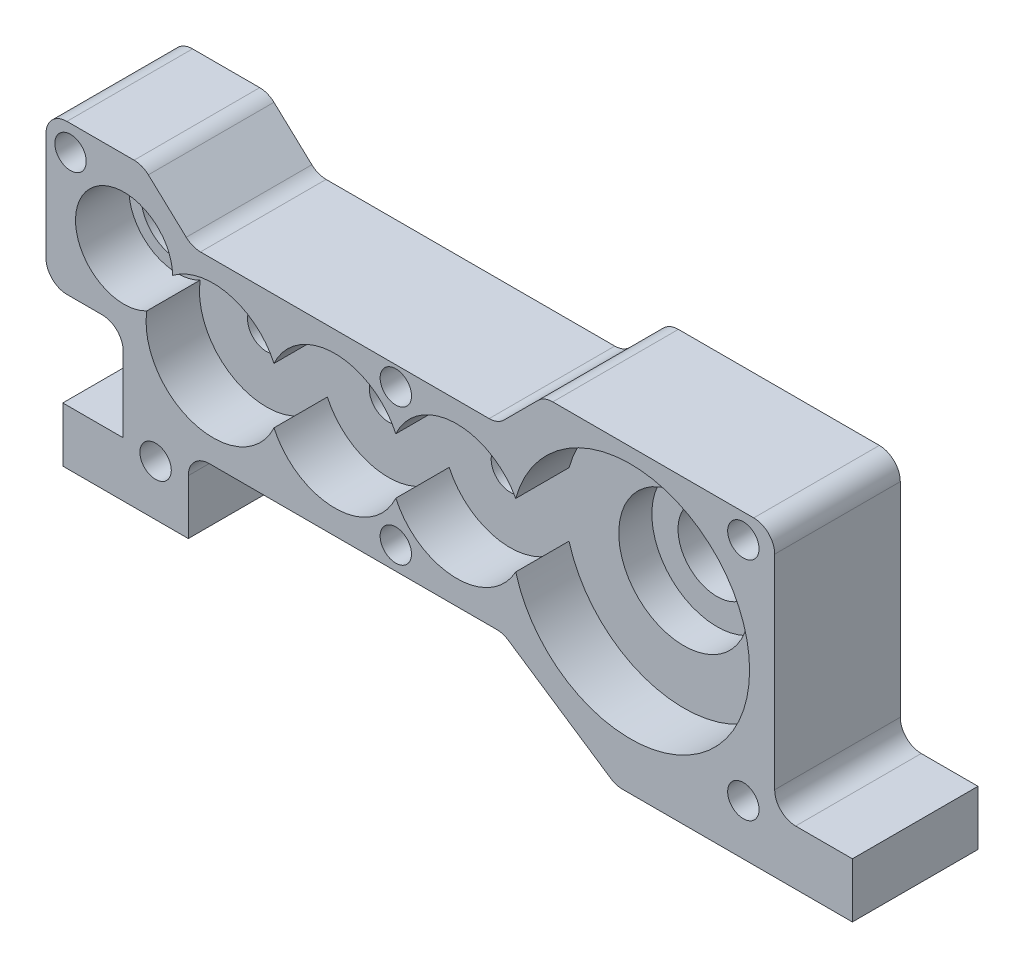
SolidWorks part; units mm, degrees
ref_plane "Front Plane" through (0, 0, 0) normal (0, 0, 1) x (1, 0, 0)
ref_plane "Top Plane" through (0, 0, 0) normal (0, 1, 0) x (1, 0, 0)
ref_plane "Right Plane" through (0, 0, 0) normal (1, 0, 0) x (0, 0, -1)
sketch "Sketch11" plane through (0, 0, 0) normal (0, 0, 1) x (1, 0, 0)
  arc A16 (19.459, 4.3148) -> (4.9137, 3.8376) centre (12.3051, 0.4566) ccw
  arc A17 (4.9137, 3.8376) -> (-9.8691, 3.8376) centre (-2.4777, 0.4566) ccw
  arc A18 (-9.8691, 3.8376) -> (-22.1638, 6.939) centre (-17.2605, 0.4566) ccw
  arc A19 (-22.1638, 6.939) -> (-25.3015, 1.6425) centre (-28.056, 6.8519) ccw
  arc A20 (-25.3015, 1.6425) -> (-9.8691, -2.9245) centre (-17.2605, 0.4566) ccw
  arc A21 (-9.8691, -2.9245) -> (4.9137, -2.9245) centre (-2.4777, 0.4566) ccw
  arc A22 (4.9137, -2.9245) -> (19.459, -3.4017) centre (12.3051, 0.4566) ccw
  arc A23 (19.459, -3.4017) -> (19.459, 4.3148) centre (33.3871, 0.4566) ccw
sketch "Sketch4" plane through (0, 0, 0) normal (0, 0, 1) x (1, 0, 0)
  line L0 (-34.99, 16.7149) -> (-26.8379, 16.7149)
  line L1 (-35.4928, -19.7615) -> (-20.2632, -19.7615)
  line L2 (22.1632, 15.9709) -> (18.0348, 11.8425)
  line L3 (-37.53, 14.1749) -> (-37.53, 1.0668)
  line L4 (50.8827, -10.5807) -> (50.8827, 14.1749)
  line L5 (60.3115, -19.7615) -> (60.3115, -13.1207)
  line L6 (60.3115, -13.1207) -> (53.4227, -13.1207)
  line L7 (-35.4928, -19.7615) -> (-35.4928, -13.1207)
  line L8 (-35.4928, -13.1207) -> (-28.1635, -13.1207)
  line L9 (-17.7232, -10.607) -> (17.1578, -10.607)
  line L10 (23.9592, 16.7149) -> (48.3427, 16.7149)
  line L11 (-20.2632, -13.147) -> (-20.2632, -19.7615)
  line L12 (32.4062, -19.7615) -> (60.3115, -19.7615)
  line L13 (16.2387, 11.0985) -> (-18.7868, 11.0985)
  line L14 (-20.5135, 11.7758) -> (-25.1112, 16.0376)
  line L16 (-34.99, -1.4732) -> (-30.7035, -1.4732)
  line L17 (-28.1635, -4.0132) -> (-28.1635, -13.1207)
  line L18 (18.5684, -11.0347) -> (30.9956, -19.3338)
  arc A0 (-34.99, 16.7149) -> (-37.53, 14.1749) centre (-34.99, 14.1749) ccw
  arc A1 (-25.1112, 16.0376) -> (-26.8379, 16.7149) centre (-26.8379, 14.1749) ccw
  arc A2 (-18.7868, 11.0985) -> (-20.5135, 11.7758) centre (-18.7868, 13.6385) cw
  arc A3 (18.0348, 11.8425) -> (16.2387, 11.0985) centre (16.2387, 13.6385) cw
  arc A4 (23.9592, 16.7149) -> (22.1632, 15.9709) centre (23.9592, 14.1749) ccw
  arc A5 (50.8827, 14.1749) -> (48.3427, 16.7149) centre (48.3427, 14.1749) ccw
  arc A6 (53.4227, -13.1207) -> (50.8827, -10.5807) centre (53.4227, -10.5807) cw
  arc A7 (30.9956, -19.3338) -> (32.4062, -19.7615) centre (32.4062, -17.2215) ccw
  arc A8 (17.1578, -10.607) -> (18.5684, -11.0347) centre (17.1578, -13.147) cw
  arc A9 (-17.7232, -10.607) -> (-20.2632, -13.147) centre (-17.7232, -13.147) ccw
  arc A10 (-30.7035, -1.4732) -> (-28.1635, -4.0132) centre (-30.7035, -4.0132) cw
  arc A11 (-37.53, 1.0668) -> (-34.99, -1.4732) centre (-34.99, 1.0668) ccw
  point P22 (-37.53, 16.7149)
  dimension "D3" = 2.54
  dimension "D2" = 2.54
  dimension "D1" = 19.7615
extrude "Extrude3" add sketch "Sketch4" against normal blind 15.24 separate body
sketch "Sketch6" plane through (0, 0, 0) normal (0, 1, 0) x (1, 0, 0)
  line L0 (-31.8281, 0) -> (-31.8281, -25.6603) construction
  line L1 (-28.1635, 0) -> (-35.4928, 0) construction
  line L2 (-29.4475, -3.81) -> (79.3394, -3.81) construction
  line L3 (56.8671, 0) -> (56.8671, -18.8958) construction
  line L4 (60.3115, 0) -> (53.4227, 0) construction
  line L5 (-35.4928, 7.62) -> (81.1858, 7.62) construction
  line L6 (-35.4928, 15.24) -> (-35.4928, 0) construction
  circle A0 centre (-30.1395, 6.985) radius 1.905
  circle A1 centre (60.5909, 6.985) radius 1.905
  circle A2 centre (60.5909, 8.255) radius 1.905
  circle A3 centre (-30.1395, 8.255) radius 1.905
  dimension "D2" = 3.81
  dimension "D1" = 3.81
sketch "Sketch1" plane through (0, 0, 0) normal (0, 0, 1) x (1, 0, 0)
  line L4 (33.3871, 0.4566) -> (12.3051, 0.4566) construction
  line L5 (-2.4777, 0.4566) -> (12.3051, 0.4566) construction
  line L6 (-2.4777, 0.4566) -> (-15.0253, 0.4566) construction
  line L7 (-15.0253, 0.4566) -> (-31.5575, 0.4566) construction
  arc A0 (19.459, 4.3148) -> (4.9137, 3.8376) centre (12.3051, 0.4566) ccw
  arc A1 (-9.8691, -2.9245) -> (4.9137, -2.9245) centre (-2.4777, 0.4566) ccw
  arc A2 (19.459, -3.4017) -> (19.459, 4.3148) centre (33.3871, 0.4566) ccw
  arc A3 (4.9137, -2.9245) -> (19.459, -3.4017) centre (12.3051, 0.4566) ccw
  arc A4 (4.9137, 3.8376) -> (-9.8691, 3.8376) centre (-2.4777, 0.4566) ccw
  arc A5 (-22.1638, 6.939) -> (-25.3015, 1.6425) centre (-28.056, 6.8519) ccw construction
  arc A6 (-9.8691, 3.8376) -> (-22.1638, 6.939) centre (-17.2605, 0.4566) ccw construction
  arc A7 (19.459, -3.4017) -> (19.459, 4.3148) centre (33.3871, 0.4566) ccw construction
  arc A8 (-22.1638, 6.939) -> (-25.3015, 1.6425) centre (-28.056, 6.8519) ccw
  arc A9 (-9.8691, 3.8376) -> (-22.1638, 6.939) centre (-17.2605, 0.4566) ccw
  arc A10 (-25.3015, 1.6425) -> (-9.8691, -2.9245) centre (-17.2605, 0.4566) ccw construction
  arc A11 (-25.3015, 1.6425) -> (-9.8691, -2.9245) centre (-17.2605, 0.4566) ccw
  dimension "D4" = 16.256
  dimension "D5" = 28.9052
  dimension "D3" = 16.256
  dimension "D13" = 12.5476
  dimension "D14" = 21.082
extrude "Extrude4" cut sketch "Sketch1" against normal blind 6.477
sketch "Sketch7" plane through (0, 0, -6.477) normal (0, 0, 1) x (1, 0, 0)
  circle A0 centre (33.3871, 0.4566) radius 7.8994
  dimension "D1" = 15.7988
extrude "Extrude5" cut sketch "Sketch7" against normal blind 4.0132
sketch "Sketch8" plane through (0, 0, -6.477) normal (0, 0, 1) x (1, 0, 0)
  circle A0 centre (12.3051, 0.4566) radius 2.2987
  circle A1 centre (-2.4777, 0.4566) radius 2.2987
  circle A2 centre (-17.2605, 0.4566) radius 2.2987
  dimension "D1" = 4.5974
extrude "Extrude6" cut sketch "Sketch8" against normal blind 4.2926
sketch "Sketch9" plane through (0, 0, -6.477) normal (0, 0, 1) x (1, 0, 0)
  circle A0 centre (-28.056, 6.8519) radius 4.4196
  dimension "D1" = 8.8392
extrude "Extrude7" cut sketch "Sketch9" against normal blind 4.4196
sketch "Sketch12" plane through (0, 0, 0) normal (0, 0, 1) x (1, 0, 0)
  circle A2 centre (-28.056, 6.8519) radius 1.1793
  circle A4 centre (-24.2337, -13.6231) radius 1.905
  circle A6 centre (47.0806, -13.6231) radius 1.905
  circle A8 centre (47.0806, 13.7746) radius 1.905
  circle A10 centre (33.3871, 0.4566) radius 4.7244
  circle A12 centre (4.9137, -7.8515) radius 1.905
  circle A14 centre (4.9137, 8.7646) radius 1.905
  circle A16 centre (-34.5549, 13.6652) radius 1.905
extrude "Extrude8" cut sketch "Sketch12" against normal mid plane 38.354
